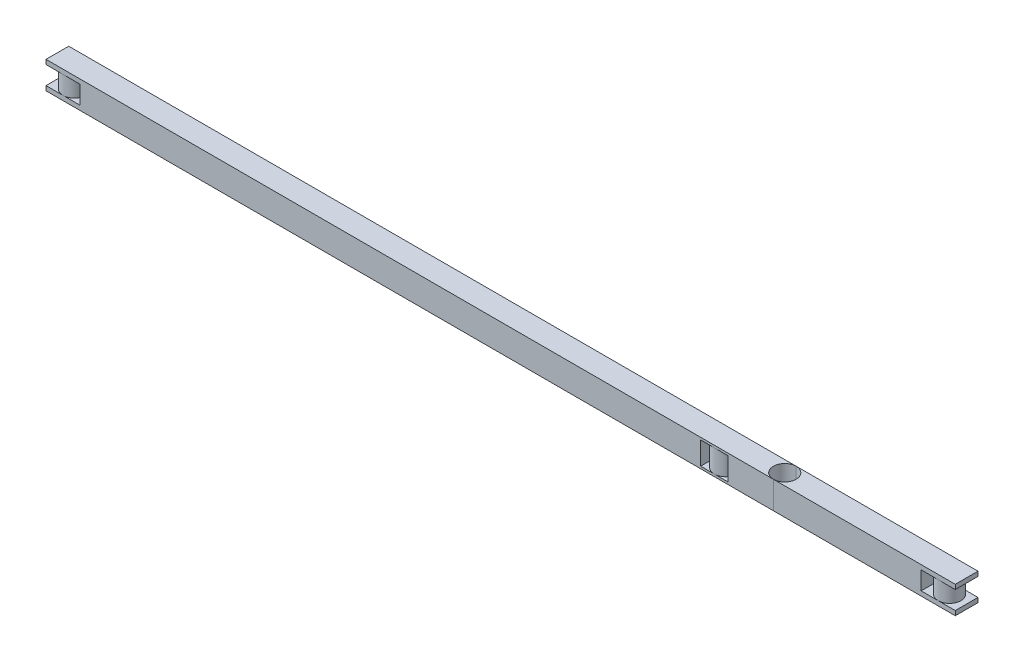
SolidWorks part; units mm, degrees
ref_plane "Front Plane" through (0, 0, 0) normal (0, 0, 1) x (1, 0, 0)
ref_plane "Top Plane" through (0, 0, 0) normal (0, 1, 0) x (1, 0, 0)
ref_plane "Right Plane" through (0, 0, 0) normal (1, 0, 0) x (0, 0, -1)
sketch "Sketch1" plane through (0, 0, 0) normal (0, 0, 1) x (1, 0, 0)
  line L0 (0, 0) -> (200, 0)
  line L1 (200, 0) -> (200, -6)
  line L2 (200, -6) -> (0, -6)
  line L3 (0, -6) -> (0, 0)
  line L4 (0, -1) -> (7.5, -1)
  line L5 (7.5, -1) -> (7.5, -5)
  line L6 (7.5, -5) -> (0, -5)
  line L7 (200, -1) -> (192.5, -1)
  line L8 (192.5, -1) -> (192.5, -5)
  line L9 (192.5, -5) -> (200, -5)
  dimension "D1" = 200
  dimension "D2" = 6
  dimension "D3" = 7.5
  dimension "D4" = 1
  dimension "D5" = 1
  dimension "D6" = 7.5
  dimension "D7" = 1
  dimension "D8" = 1
extrude "Boss-Extrude1" add sketch "Sketch1" along normal blind 5 contours L9 L8 L7 L1 L0 L3 L4 L5 L6 L2
sketch "Sketch2" plane through (0, -6, 0) normal (0, -1, 0) x (1, 0, 0)
  line L0 (0, 5) -> (0, 0) construction
  line L1 (200, 5) -> (0, 5) construction
  circle A0 centre (3.75, 2.5) radius 2.5
  dimension "D3" = 5
  dimension "D1" = 3.75
  dimension "D2" = 2.5
extrude "Boss-Extrude2" add sketch "Sketch2" against normal up to surface (5 mm away) contours A0 up to face at (3.75, -1, 2.5)
sketch "Sketch4" plane through (0, 0, 0) normal (0, 1, 0) x (1, 0, 0)
  line L2 (0, -5) -> (200, -5) construction
  line L3 (200, -5) -> (200, 0) construction
  circle A0 centre (196.25, -2.5) radius 2.5
  dimension "D1" = 5
  dimension "D2" = 2.5
  dimension "D3" = 3.75
extrude "Boss-Extrude3" add sketch "Sketch4" against normal up to surface (5 mm away) up to face at (196.25, -5, 2.5)
ref_plane "Plane1" through (0, -3, 0) normal (0, 1, 0) x (1, 0, 0)
sketch "Sketch8" plane through (0, -3, 0) normal (0, 1, 0) x (1, 0, 0)
  line L0 (144, 0) -> (144, -6)
  line L1 (144, -6) -> (150, -6)
  line L2 (150, -6) -> (150, 0)
  line L3 (150, 0) -> (144, 0)
  line L4 (0, 0) -> (200, 0) construction
  line L5 (200, -5) -> (200, 0) construction
  dimension "D1" = 6
  dimension "D2" = 6
  dimension "D3" = 50
extrude "Cut-Extrude9" cut sketch "Sketch8" against normal mid plane 5
sketch "Sketch9" plane through (0, -5.5, 0) normal (0, 1, 0) x (1, 0, 0)
  line L0 (0, 0) -> (200, 0) construction
  line L1 (150, -5) -> (150, 0) construction
  circle A0 centre (147, -2.5) radius 2.5
  dimension "D1" = 5
  dimension "D2" = 3
extrude "Boss-Extrude4" add sketch "Sketch9" along normal up to next
sketch "Sketch10" plane through (0, 0, 0) normal (0, 1, 0) x (1, 0, 0)
  line L0 (0, 0) -> (200, 0) construction
  line L1 (200, -5) -> (200, 0) construction
  circle A0 centre (160, -2.5) radius 2.5
  dimension "D1" = 5
  dimension "D2" = 40
extrude "Cut-Extrude10" cut sketch "Sketch10" against normal through all
